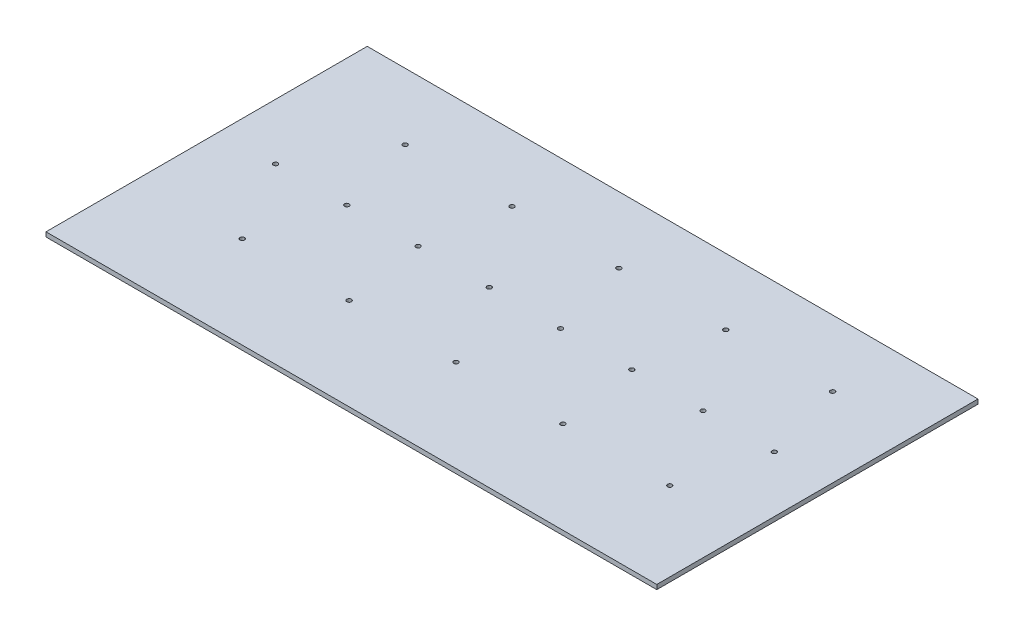
SolidWorks part; units mm, degrees
ref_plane "Front Plane" through (0, 0, 0) normal (0, 0, 1) x (1, 0, 0)
ref_plane "Top Plane" through (0, 0, 0) normal (0, 1, 0) x (1, 0, 0)
ref_plane "Right Plane" through (0, 0, 0) normal (1, 0, 0) x (0, 0, -1)
sketch "Sketch1" plane through (0, 0, 0) normal (0, 1, 0) x (1, 0, 0)
  line L1 (0, 0) -> (857.25, 0)
  line L2 (0, 0) -> (0, 450.85)
  line L3 (0, 450.85) -> (857.25, 450.85)
  line L4 (857.25, 0) -> (857.25, 450.85)
  dimension "D1" = 450.85
  dimension "D2" = 857.25
extrude "Boss-Extrude1" add sketch "Sketch1" along normal blind 6.35
sketch "Sketch2" plane through (0, 6.35, 0) normal (0, 1, 0) x (1, 0, 0)
  line L0 (78.625, 243.5678) -> (0, 243.5678) construction
  line L1 (0, 450.85) -> (0, 0) construction
  line L2 (778.625, 243.5678) -> (857.25, 243.5678) construction
  line L3 (78.625, 243.5678) -> (178.625, 243.5678) construction
  line L4 (146.163, 357.8678) -> (0, 357.8678) construction
  line L5 (857.25, 0) -> (857.25, 450.85) construction
  line L6 (178.625, 243.5678) -> (278.625, 243.5678) construction
  line L7 (278.625, 243.5678) -> (378.625, 243.5678) construction
  line L8 (378.625, 243.5678) -> (478.625, 243.5678) construction
  line L9 (478.625, 243.5678) -> (578.625, 243.5678) construction
  line L10 (578.625, 243.5678) -> (678.625, 243.5678) construction
  line L11 (678.625, 243.5678) -> (778.625, 243.5678) construction
  line L12 (146.163, 357.8678) -> (296.163, 357.8678) construction
  line L13 (296.163, 357.8678) -> (446.163, 357.8678) construction
  line L14 (446.163, 357.8678) -> (596.163, 357.8678) construction
  line L15 (596.163, 357.8678) -> (746.163, 357.8678) construction
  line L16 (746.163, 357.8678) -> (857.25, 357.8678) construction
  line L17 (146.163, 129.2678) -> (0, 129.2678) construction
  line L18 (146.163, 129.2678) -> (296.163, 129.2678) construction
  line L19 (296.163, 129.2678) -> (296.1632, 129.0266) construction
  line L20 (296.1632, 129.0266) -> (446.163, 129.2678) construction
  line L21 (446.163, 129.2678) -> (596.163, 129.2678) construction
  line L22 (596.163, 129.2678) -> (746.163, 129.2678) construction
  line L23 (746.163, 129.2678) -> (857.25, 129.2678) construction
  circle A0 centre (78.625, 243.5678) radius 3.175
  circle A2 centre (178.625, 243.5678) radius 3.175
  circle A3 centre (278.625, 243.5678) radius 3.175
  circle A4 centre (378.625, 243.5678) radius 3.175
  circle A5 centre (478.625, 243.5678) radius 3.175
  circle A6 centre (578.625, 243.5678) radius 3.175
  circle A7 centre (678.625, 243.5678) radius 3.175
  circle A8 centre (778.625, 243.5678) radius 3.175
  circle A11 centre (146.163, 357.8678) radius 3.175
  circle A12 centre (296.163, 357.8678) radius 3.175
  circle A13 centre (446.163, 357.8678) radius 3.175
  circle A14 centre (596.163, 357.8678) radius 3.175
  circle A15 centre (746.163, 357.8678) radius 3.175
  circle A16 centre (146.163, 129.2678) radius 3.175
  circle A17 centre (296.163, 129.2678) radius 3.175
  circle A18 centre (446.163, 129.2678) radius 3.175
  circle A19 centre (596.163, 129.2678) radius 3.175
  circle A20 centre (746.163, 129.2678) radius 3.175
  dimension "D1" = 6.35
  dimension "D4" = 150
  dimension "D2" = 100
  dimension "D3" = 114.3
  dimension "D5" = 111.087
  dimension "D6" = 114.3
  dimension "D7" = 150
extrude "Cut-Extrude1" cut sketch "Sketch2" against normal through all both and the other way through all
